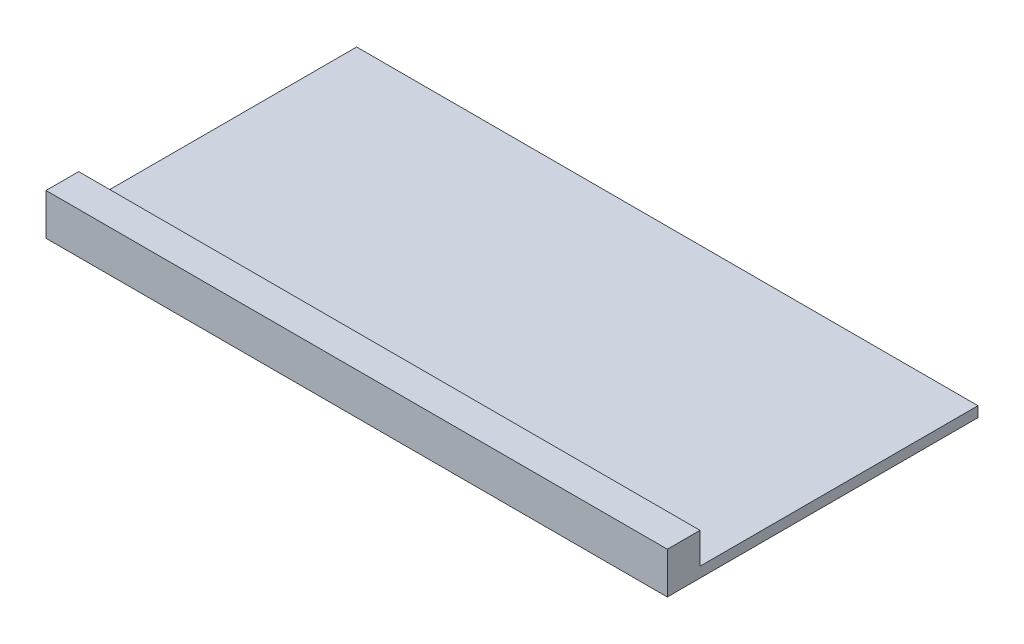
SolidWorks part; units mm, degrees
ref_plane "Front Plane" through (0, 0, 0) normal (0, 0, 1) x (1, 0, 0)
ref_plane "Top Plane" through (0, 0, 0) normal (0, 1, 0) x (1, 0, 0)
ref_plane "Right Plane" through (0, 0, 0) normal (1, 0, 0) x (0, 0, -1)
sketch "Sketch1" plane through (0, 0, 0) normal (0, 1, 0) x (1, 0, 0)
  line L1 (150, -75) -> (-150, -75)
  line L2 (150, -75) -> (150, 75)
  line L3 (150, 75) -> (-150, 75)
  line L4 (-150, -75) -> (-150, 75)
  line L5 (150, -75) -> (-150, 75) construction
  line L6 (150, 75) -> (-150, -75) construction
  point P0 (0, 0)
  dimension "D1" = 300
  dimension "D2" = 150
extrude "Boss-Extrude1" add sketch "Sketch1" along normal blind 5
sketch "Sketch2" plane through (0, 5, 0) normal (0, 1, 0) x (1, 0, 0)
  line L0 (-150, -75) -> (150, -75) construction
  line L1 (-150, -75) -> (150, -75)
  line L2 (-150, -75) -> (-150, -59.224)
  line L3 (-150, 75) -> (-150, -75) construction
  line L4 (-150, -59.224) -> (150, -59.224)
  line L5 (150, -75) -> (150, 75) construction
  line L6 (150, -59.224) -> (150, -75)
extrude "Boss-Extrude2" add sketch "Sketch2" along normal blind 15
